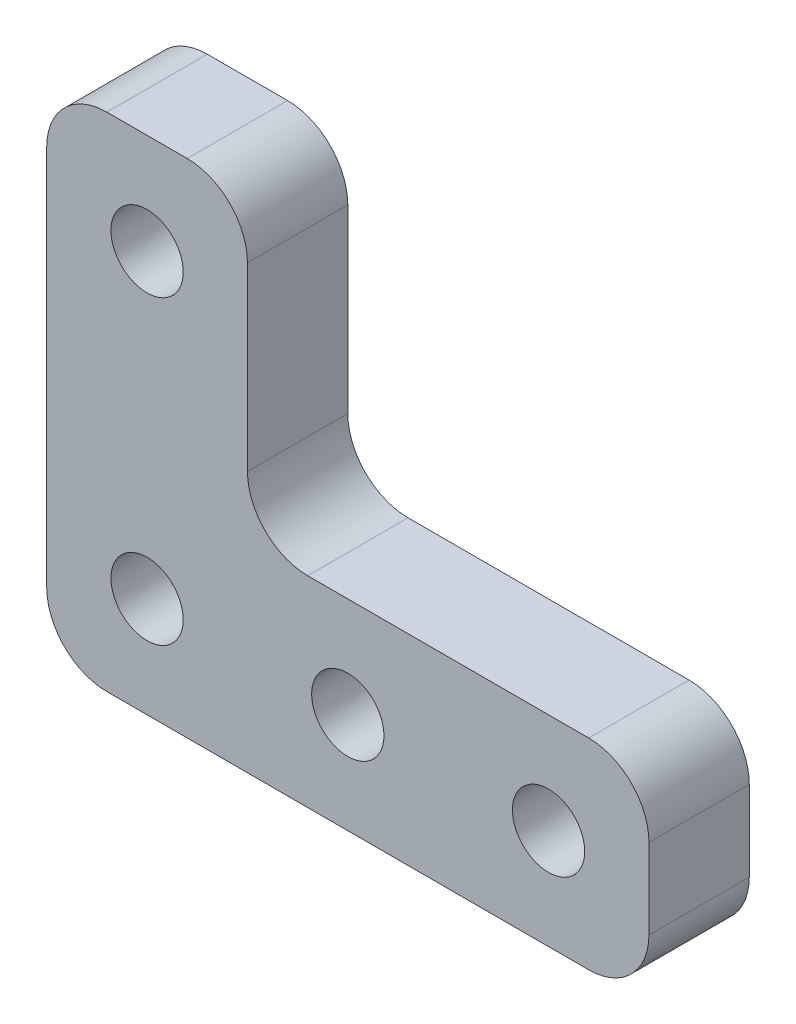
SolidWorks part; units mm, degrees
ref_plane "Front Plane" through (0, 0, 0) normal (0, 0, 1) x (1, 0, 0)
ref_plane "Top Plane" through (0, 0, 0) normal (0, 1, 0) x (1, 0, 0)
ref_plane "Right Plane" through (0, 0, 0) normal (1, 0, 0) x (0, 0, -1)
sketch "Sketch1" plane through (0, 0, 0) normal (0, 0, 1) x (1, 0, 0)
  line L0 (-6.35, -6.35) -> (-6.35, 25.4)
  line L1 (-6.35, 25.4) -> (6.35, 25.4)
  line L2 (6.35, 25.4) -> (6.35, 6.35)
  line L3 (6.35, 6.35) -> (31.75, 6.35)
  line L4 (31.75, 6.35) -> (31.75, -6.35)
  line L5 (31.75, -6.35) -> (-6.35, -6.35)
  circle A0 centre (0, 0) radius 2.286
  circle A1 centre (12.7, 0) radius 2.286
  circle A2 centre (25.4, 0) radius 2.286
  circle A3 centre (0, 19.05) radius 2.286
  point P5 (6.35, 31.75)
  point P16 (0, 0)
  point P17 (0, 0)
  dimension "D1" = 4.572
  dimension "D5" = 3
  dimension "D2" = 6.35
  dimension "D3" = 6.35
  dimension "D4" = 12.7
  dimension "D7" = 6.35
  dimension "D8" = 38.1
  dimension "D9" = 19.05
  dimension "D6" = 1
extrude "Boss-Extrude1" add sketch "Sketch1" along normal blind 6.35
fillet "Fillet1" radius 3.81 6 edges at (31.75, 6.35, 3.175) (31.75, -6.35, 3.175) (-6.35, -6.35, 3.175) (-6.35, 25.4, 3.175) (6.35, 25.4, 3.175) (6.35, 6.35, 3.175)
